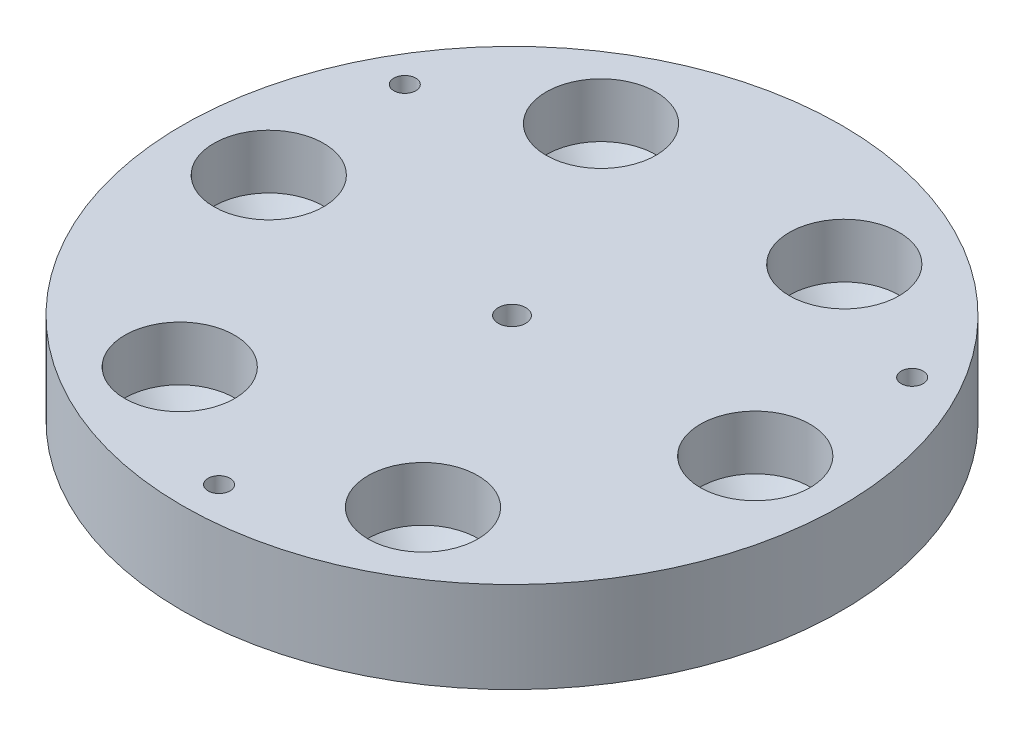
SolidWorks part; units mm, degrees
ref_plane "Front Plane" through (0, 0, 0) normal (0, 0, 1) x (1, 0, 0)
ref_plane "Top Plane" through (0, 0, 0) normal (0, 1, 0) x (1, 0, 0)
ref_plane "Right Plane" through (0, 0, 0) normal (1, 0, 0) x (0, 0, -1)
sketch "Sketch1" plane through (0, 0, 0) normal (0, 1, 0) x (1, 0, 0)
  circle A0 centre (0, 0) radius 45
  dimension "D1" = 90
extrude "Boss-Extrude1" add sketch "Sketch1" against normal blind 2 and the other way blind 10.4254 contours A0
sketch "Sketch2" plane through (0, 10.4254, 0) normal (0, 1, 0) x (1, 0, 0)
  circle A0 centre (0, 0) radius 33.2139
  circle A1 centre (0, 0) radius 1.875
  point P3 (16.607, 28.7641)
  point P4 (-16.607, 28.7641)
  point P5 (-33.2139, 0)
  point P6 (-16.607, -28.7641)
  point P7 (16.607, -28.7641)
  point P8 (33.2139, 0)
hole_wizard "Ø8.0mm Dowel Hole1" positions "Sketch3" profile "Sketch4" hole size "Ø8.0" standard "ANSI Metric"
sketch "Sketch3" plane through (0, 10.4254, 0) normal (0, 1, 0) x (1, 0, 0)
  point P0 (-16.607, 28.7641)
  point P3 (-16.607, -28.7641)
  point P6 (33.2139, 0)
  point P9 (16.607, 28.7641)
  point P12 (16.607, -28.7641)
  point P15 (-33.2139, 0)
sketch "Sketch4" plane through (-16.607, 10.4254, -28.7641) normal (1, 0, 0) x (0, 0, 1)
  line L0 (0, 0) -> (0, 14.9254)
  line L1 (0, 14.9254) -> (7.5, 7.4254)
  line L2 (7.5, 7.4254) -> (7.5, 0)
  line L5 (7.5, 0) -> (0, 0)
  line L10 (0, 14.9254) -> (-7.5, 7.4254) construction
  line L11 (0, -6.35) -> (0, 107.95) construction
  dimension "Hole Dia." = 15
  dimension "Hole Depth" = 7.4254
  dimension "Drill Angle" = 90
sketch "Sketch10" plane through (0, 10.4254, 0) normal (0, 1, 0) x (1, 0, 0)
  circle A0 centre (0, 0) radius 40
  point P3 (-34.641, 20)
  point P4 (0, -40)
  point P5 (34.641, 20)
hole_wizard "Ø3.0 (3) Diameter Hole1" positions "Sketch11" profile "Sketch12" hole size "Ø3.0" standard "ANSI Metric" end condition through all
sketch "Sketch11" plane through (0, 10.4254, 0) normal (0, 1, 0) x (1, 0, 0)
  point P0 (-34.641, 20)
  point P3 (0, -40)
  point P6 (34.641, 20)
sketch "Sketch12" plane through (-34.641, 10.4254, -20) normal (1, 0, 0) x (0, 0, 1)
  line L0 (0, 0) -> (0, 12.4254)
  line L1 (0, 12.4254) -> (1.5, 12.4254)
  line L2 (1.5, 12.4254) -> (1.5, 0)
  line L5 (1.5, 0) -> (0, 0)
  line L11 (0, -6.35) -> (0, 107.95) construction
  dimension "Thru Hole Dia." = 3
  dimension "Thru Hole Depth" = 12.4254
extrude "Cut-Extrude1" cut sketch "Sketch2" against normal blind 15 contours A1
